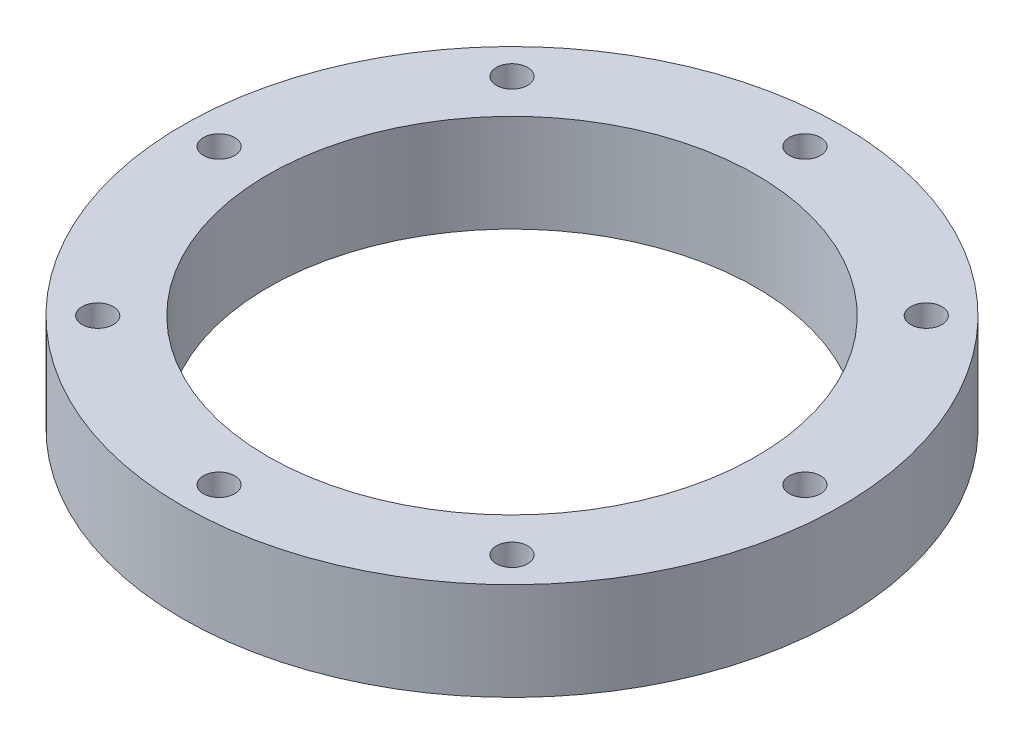
SolidWorks part; units mm, degrees
ref_plane "前视基准面" through (0, 0, 0) normal (0, 0, 1) x (1, 0, 0)
ref_plane "上视基准面" through (0, 0, 0) normal (0, 1, 0) x (1, 0, 0)
ref_plane "右视基准面" through (0, 0, 0) normal (1, 0, 0) x (0, 0, -1)
sketch "草图1" plane through (0, 0, 0) normal (0, 1, 0) x (1, 0, 0)
  circle A0 centre (0, 0) radius 50
  circle A1 centre (0, 0) radius 67.5
  dimension "D1" = 100
  dimension "D2" = 135
extrude "凸台-拉伸1" add sketch "草图1" along normal blind 20
sketch "草图2" plane through (0, 20, 0) normal (0, 1, 0) x (1, 0, 0)
  circle A0 centre (0, 0) radius 60 construction
  circle A1 centre (0, 60) radius 3.2
  circle A2 centre (42.4264, 42.4264) radius 3.2
  circle A3 centre (60, 0) radius 3.2
  circle A4 centre (42.4264, -42.4264) radius 3.2
  circle A5 centre (0, -60) radius 3.2
  circle A6 centre (-42.4264, -42.4264) radius 3.2
  circle A7 centre (-60, 0) radius 3.2
  circle A8 centre (-42.4264, 42.4264) radius 3.2
  point P21 (0, 0)
  dimension "D1" = 120
  dimension "D2" = 6.4
  dimension "D3" = 8
extrude "切除-拉伸1" cut sketch "草图2" against normal blind 20
cosmetic thread "装饰螺纹线1" parameters "D2"=10
cosmetic thread "装饰螺纹线2" parameters "D2"=10
cosmetic thread "装饰螺纹线3" parameters "D2"=10
cosmetic thread "装饰螺纹线4" parameters "D2"=10
cosmetic thread "装饰螺纹线5" parameters "D2"=10
cosmetic thread "装饰螺纹线6" parameters "D2"=10
cosmetic thread "装饰螺纹线7" parameters "D2"=10
cosmetic thread "装饰螺纹线8" parameters "D2"=10
